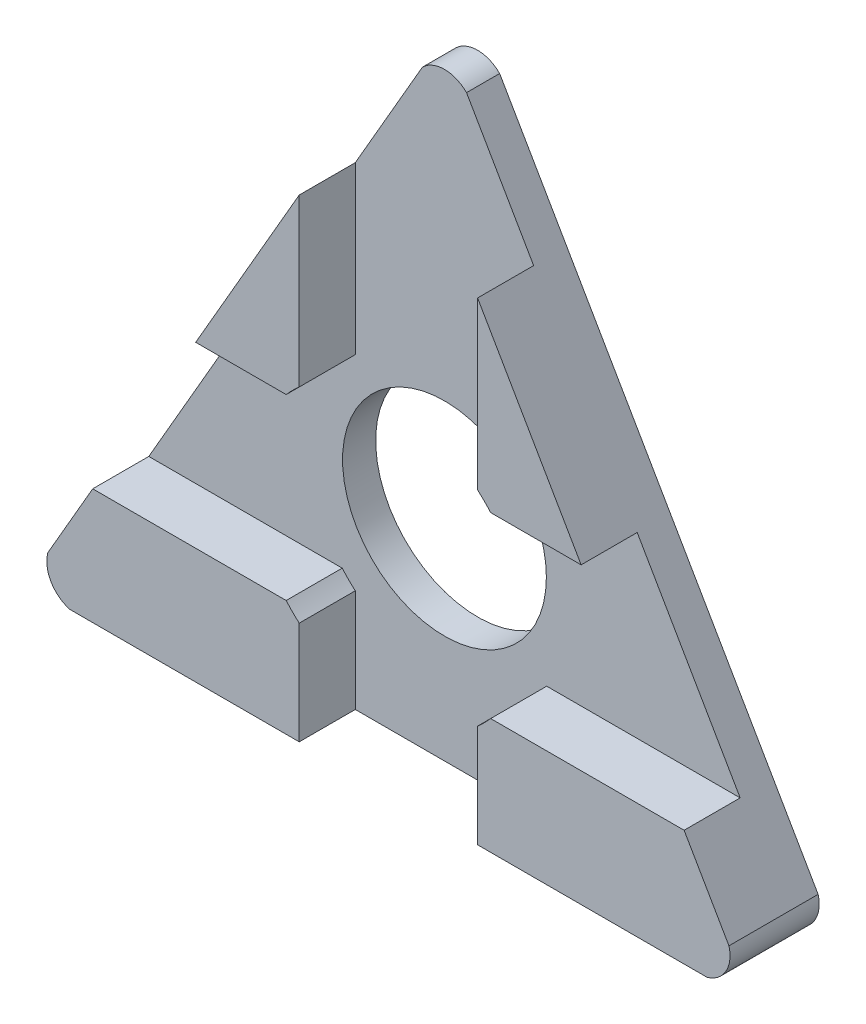
SolidWorks part; units mm, degrees
ref_plane "正面" through (0, 0, 0) normal (0, 0, 1) x (1, 0, 0)
ref_plane "平面" through (0, 0, 0) normal (0, 1, 0) x (1, 0, 0)
ref_plane "右側面" through (0, 0, 0) normal (1, 0, 0) x (0, 0, -1)
sketch "ｽｹｯﾁ1" plane through (0, 0, 0) normal (0, 0, 1) x (1, 0, 0)
  line L0 (0, 21.6506) -> (-12.5, 0)
  line L1 (-12.5, 0) -> (12.5, 0)
  line L2 (12.5, 0) -> (0, 21.6506)
  dimension "D1" = 25
extrude "ﾎﾞｽ - 押し出し1" add sketch "ｽｹｯﾁ1" along normal blind 3.5
sketch "ｽｹｯﾁ11" plane through (0, 0, 0) normal (0, 0, -1) x (-1, 0, 0)
  line L0 (0, 21.6506) -> (12.5, 0)
  line L1 (0, 21.6506) -> (0.866, 22.1506) construction
  line L2 (-0.866, 22.1506) -> (0, 21.6506) construction
  line L3 (0.866, 22.1506) -> (13.366, 0.5)
  line L4 (12.5, 0) -> (-12.5, 0)
  line L5 (-13.366, 0.5) -> (-12.5, 0) construction
  line L6 (-12.5, 0) -> (-12.5, -1) construction
  line L7 (12.5, -1) -> (-12.5, -1)
  line L8 (0, 21.6506) -> (-12.5, 0)
  line L9 (12.5, 0) -> (12.5, -1) construction
  line L10 (12.5, 0) -> (13.366, 0.5) construction
  line L11 (-0.866, 22.1506) -> (-13.366, 0.5)
  arc A0 (-0.866, 22.1506) -> (0.866, 22.1506) centre (0, 21.2846) cw
  arc A1 (13.366, 0.5) -> (12.5, -1) centre (12.183, 0.183) cw
  arc A2 (-12.5, -1) -> (-13.366, 0.5) centre (-12.183, 0.183) cw
  dimension "D1" = 25
  dimension "D2" = 1
  dimension "D3" = 25
  dimension "D4" = 1
  dimension "D5" = 25
  dimension "D6" = 1
extrude "ﾎﾞｽ - 押し出し8" add sketch "ｽｹｯﾁ11" against normal through all
sketch "ｽｹｯﾁ12" plane through (0, 0, 3.5) normal (0, 0, 1) x (1, 0, 0)
  line L0 (0, 7.2433) -> (-6.7011, 12.044) construction
  line L1 (-13.366, 0.5) -> (-0.866, 22.1506) construction
  line L2 (0, 7.2433) -> (6.7011, 12.044) construction
  line L3 (0.866, 22.1506) -> (13.366, 0.5) construction
  line L4 (0, 7.2433) -> (0, -1) construction
  line L6 (12.5, -1) -> (-12.5, -1) construction
  circle A0 centre (0, 7.2433) radius 4
  dimension "D1" = 8
extrude "ｶｯﾄ - 押し出し1" cut sketch "ｽｹｯﾁ12" against normal through all
sketch "ｽｹｯﾁ13" plane through (0, 0, 3.5) normal (0, 0, 1) x (1, 0, 0)
  line L0 (0, 7.2169) -> (7.116, 11.3253) construction
  line L1 (0.866, 22.1506) -> (13.366, 0.5) construction
  line L2 (0, 7.2169) -> (0, -1) construction
  line L3 (12.5, -1) -> (-12.5, -1) construction
  line L4 (0, 7.2169) -> (-7.116, 11.3253) construction
  line L5 (-13.366, 0.5) -> (-0.866, 22.1506) construction
  circle A0 centre (0, 7.0488) radius 5.325
  dimension "D1" = 10.65
extrude "ｶｯﾄ - 押し出し2" cut sketch "ｽｹｯﾁ13" against normal blind 2.2
sketch "ｽｹｯﾁ14" plane through (0, 0, 3.5) normal (0, 0, 1) x (1, 0, 0)
  line L0 (0, 7.0488) -> (3.5, 10.5488) construction
  line L1 (-3.5, 24.8699) -> (3.5, 24.8699)
  line L2 (-3.5, 10.5488) -> (-3.5, 24.8699)
  line L3 (-3.5, -2.871) -> (3.5, -2.871)
  line L4 (3.5, 10.5488) -> (3.5, 24.8699)
  line L5 (20.8756, 3.5488) -> (3.5, 3.5488)
  line L6 (-19.259, 10.5488) -> (-19.259, 3.5488)
  line L7 (20.8756, 10.5488) -> (3.5, 10.5488)
  line L8 (20.8756, 10.5488) -> (20.8756, 3.5488)
  line L9 (0, 7.0488) -> (-3.5, 10.5488) construction
  line L10 (-19.259, 10.5488) -> (-3.5, 10.5488)
  line L11 (-19.259, 3.5488) -> (-3.5, 3.5488)
  line L12 (3.5, 3.5488) -> (3.5, -2.871)
  line L13 (-3.5, 3.5488) -> (-3.5, -2.871)
  line L14 (0, 7.0488) -> (-3.5, 3.5488) construction
  line L15 (3.5, 3.5488) -> (0, 7.0488) construction
  dimension "D3" = 7
  dimension "D1" = 7
  dimension "D2" = 7
extrude "ｶｯﾄ - 押し出し3" cut sketch "ｽｹｯﾁ14" against normal blind 2.2
